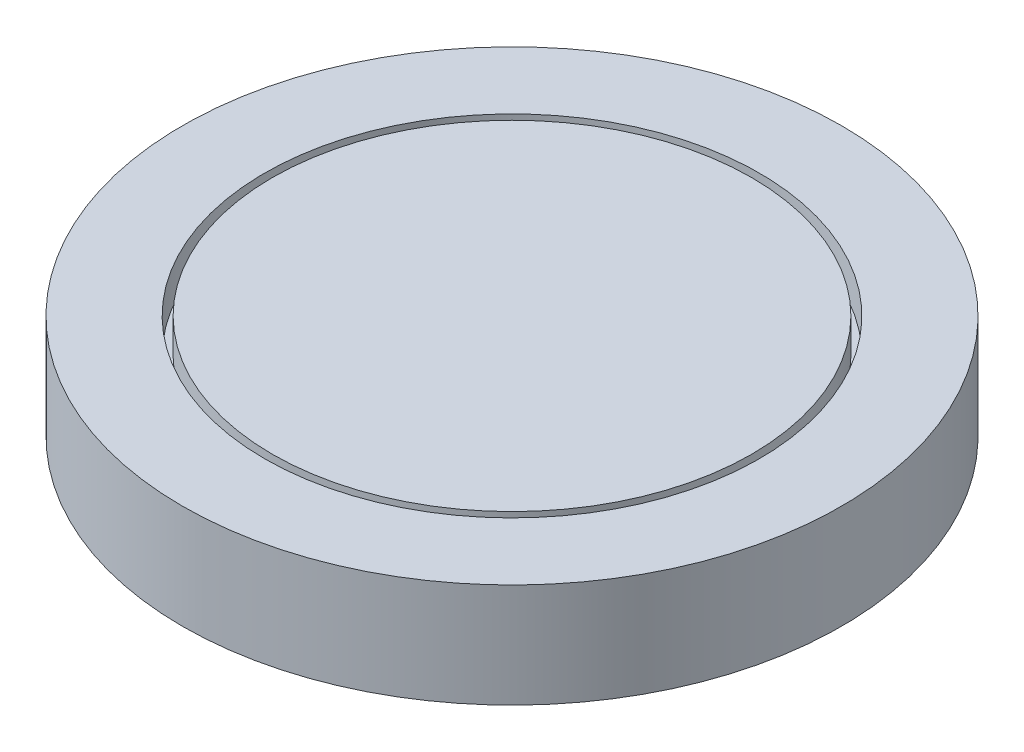
SolidWorks part; units mm, degrees
ref_plane "前视基准面" through (0, 0, 0) normal (0, 0, 1) x (1, 0, 0)
ref_plane "上视基准面" through (0, 0, 0) normal (0, 1, 0) x (1, 0, 0)
ref_plane "右视基准面" through (0, 0, 0) normal (1, 0, 0) x (0, 0, -1)
sketch "草图1" plane through (0, 0, 0) normal (0, 1, 0) x (1, 0, 0)
  circle A0 centre (0, 0) radius 9.5
  dimension "D1" = 19
extrude "凸台-拉伸1" add sketch "草图1" along normal blind 3
sketch "草图2" plane through (0, 3, 0) normal (0, 1, 0) x (1, 0, 0)
  circle A0 centre (0, 0) radius 7.1321
extrude "切除-拉伸1" cut sketch "草图2" against normal blind 1
sketch "草图3" plane through (0, 2, 0) normal (0, 1, 0) x (1, 0, 0)
  circle A0 centre (0, 0) radius 6.9082
extrude "凸台-拉伸2" add sketch "草图3" along normal blind 1
